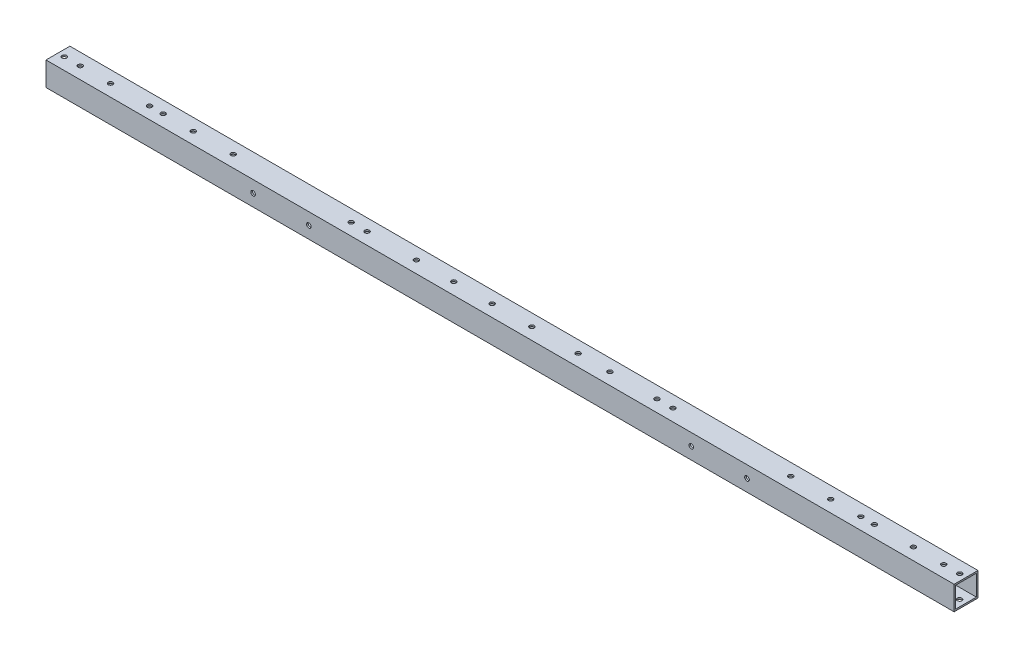
SolidWorks part; units mm, degrees
material "Thornel Mat VMA"
ref_plane "前视基准面" through (0, 0, 0) normal (0, 0, 1) x (1, 0, 0)
ref_plane "上视基准面" through (0, 0, 0) normal (0, 1, 0) x (1, 0, 0)
ref_plane "右视基准面" through (0, 0, 0) normal (1, 0, 0) x (0, 0, -1)
other "Configuration Table"
sketch "草图1" plane through (0, 0, 0) normal (1, 0, 0) x (0, 0, -1)
  line L0 (-6.5, -6.5) -> (-6.5, 6.5)
  line L1 (-7.5, -7.5) -> (7.5, -7.5)
  line L2 (-7.5, -7.5) -> (-7.5, 7.5)
  line L3 (-7.5, 7.5) -> (7.5, 7.5)
  line L4 (7.5, -7.5) -> (7.5, 7.5)
  line L5 (-7.5, -7.5) -> (7.5, 7.5) construction
  line L6 (-7.5, 7.5) -> (7.5, -7.5) construction
  line L7 (-6.5, 6.5) -> (6.5, 6.5)
  line L8 (6.5, -6.5) -> (6.5, 6.5)
  line L9 (-6.5, -6.5) -> (6.5, -6.5)
  point P0 (0, 0)
  dimension "D1" = 15
  dimension "D2" = 15
  dimension "D3" = 1
extrude "凸台-拉伸1" add sketch "草图1" along normal blind 570
sketch "草图2" plane through (0, 7.5, 0) normal (0, 1, 0) x (1, 0, 0)
  line L0 (0, 0) -> (606.0643, 0) construction
  circle A0 centre (566, 0) radius 1.45 construction
  circle A1 centre (556, 0) radius 1.45 construction
  circle A2 centre (485, 0) radius 1.45 construction
  circle A3 centre (460, 0) radius 1.45 construction
  circle A4 centre (297.5, 0) radius 1.45 construction
  circle A5 centre (272.5, 0) radius 1.45 construction
  circle A6 centre (110, 0) radius 1.45 construction
  circle A7 centre (85, 0) radius 1.45 construction
  circle A8 centre (14, 0) radius 1.45 construction
  circle A9 centre (4, 0) radius 1.45 construction
  circle A10 centre (566, 0) radius 1.45
  circle A11 centre (556, 0) radius 1.45
  circle A12 centre (485, 0) radius 1.45
  circle A13 centre (460, 0) radius 1.45
  circle A14 centre (297.5, 0) radius 1.45
  circle A15 centre (272.5, 0) radius 1.45
  circle A16 centre (110, 0) radius 1.45
  circle A17 centre (85, 0) radius 1.45
  circle A18 centre (14, 0) radius 1.45
  circle A19 centre (4, 0) radius 1.45
  circle A20 centre (512.5, 0) radius 1.45 construction
  circle A21 centre (57.5, 0) radius 1.45 construction
  circle A22 centre (512.5, 0) radius 1.45
  circle A23 centre (57.5, 0) radius 1.45
  circle A24 centre (504, 0) radius 1.45 construction
  circle A25 centre (537, 0) radius 1.45 construction
  circle A26 centre (66, 0) radius 1.45 construction
  circle A27 centre (33, 0) radius 1.45 construction
  circle A28 centre (504, 0) radius 1.45
  circle A29 centre (537, 0) radius 1.45
  circle A30 centre (66, 0) radius 1.45
  circle A31 centre (33, 0) radius 1.45
  circle A32 centre (225, 0) radius 1.45 construction
  circle A33 centre (346.5, 0) radius 1.45 construction
  circle A34 centre (225, 0) radius 1.45
  circle A35 centre (346.5, 0) radius 1.45
  circle A36 centre (326.5, 0) radius 1.45 construction
  circle A37 centre (248.5, 0) radius 1.45 construction
  circle A38 centre (326.5, 0) radius 1.45
  circle A39 centre (248.5, 0) radius 1.45
  circle A40 centre (184, 0) radius 1.45
  circle A41 centre (194, 0) radius 1.45
  circle A42 centre (376, 0) radius 1.45
  circle A43 centre (386, 0) radius 1.45
  dimension "D1" = 31
  dimension "D2" = 10
  dimension "D3" = 2.9
  dimension "D4" = 2.9
  dimension "D5" = 2.9
  dimension "D6" = 2.9
  dimension "D7" = 29.5
  dimension "D8" = 39.5
extrude "切除-拉伸1" cut sketch "草图2" against normal through all
sketch "草图3" plane through (0, 0, -7.5) normal (0, 0, -1) x (-1, 0, 0)
  circle A0 centre (-130, 0) radius 1.45 construction
  circle A1 centre (-165, 0) radius 1.45 construction
  circle A2 centre (-405, 0) radius 1.45 construction
  circle A3 centre (-440, 0) radius 1.45 construction
  circle A4 centre (-130, 0) radius 1.45
  circle A5 centre (-165, 0) radius 1.45
  circle A6 centre (-405, 0) radius 1.45
  circle A7 centre (-440, 0) radius 1.45
extrude "切除-拉伸2" cut sketch "草图3" against normal through all
